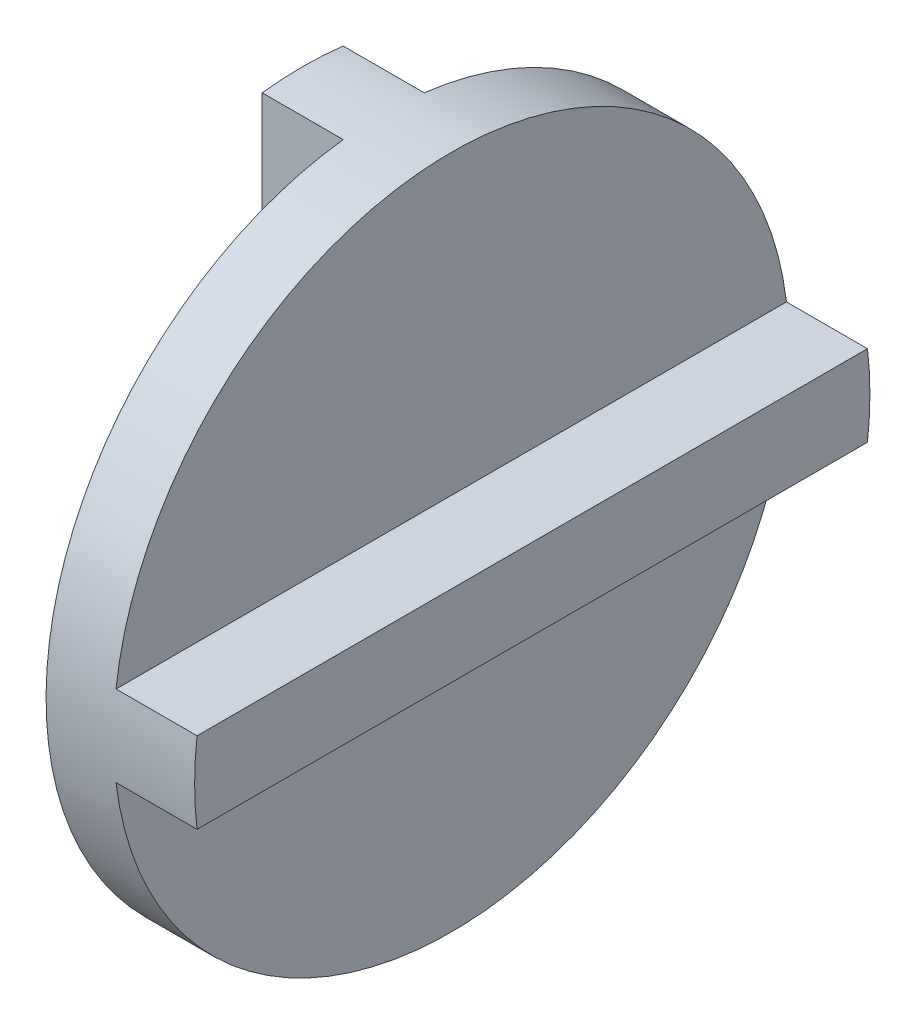
SolidWorks part; units mm, degrees
material "ABS"
ref_plane "Front Plane" through (0, 0, 0) normal (0, 0, 1) x (1, 0, 0)
ref_plane "Top Plane" through (0, 0, 0) normal (0, 1, 0) x (1, 0, 0)
ref_plane "Right Plane" through (0, 0, 0) normal (1, 0, 0) x (0, 0, -1)
sketch "Sketch1" plane through (0, 0, 0) normal (1, 0, 0) x (0, 0, -1)
  circle A0 centre (0, 0) radius 50
  dimension "D1" = 100
extrude "Boss-Extrude1" add sketch "Sketch1" along normal blind 10
sketch "Sketch2" plane through (10, 0, 0) normal (1, 0, 0) x (0, 0, -1)
  line L1 (-49.6387, 6) -> (49.6387, 6)
  line L3 (-49.6387, -6) -> (49.6387, -6)
  circle A0 centre (0, 0) radius 50 construction
  arc A1 (-49.6387, 6) -> (-49.6387, -6) centre (0, 0) ccw
  arc A2 (49.6387, -6) -> (49.6387, 6) centre (0, 0) ccw
  dimension "D1" = 12
  dimension "D2" = 6
extrude "Boss-Extrude2" add sketch "Sketch2" along normal blind 12
sketch "Sketch3" plane through (0, 0, 0) normal (-1, 0, 0) x (0, 0, 1)
  line L2 (-6, 49.6387) -> (-6, -49.6387)
  line L4 (6, 49.6387) -> (6, -49.6387)
  circle A0 centre (0, 0) radius 50 construction
  arc A1 (-6, -49.6387) -> (-6, 49.6387) centre (0, 0) ccw
  circle M1 centre (0, 0) radius 50
  dimension "D1" = 6
  dimension "D2" = 12
extrude "Boss-Extrude3" add sketch "Sketch3" along normal blind 12 contours L4 L2 M1
